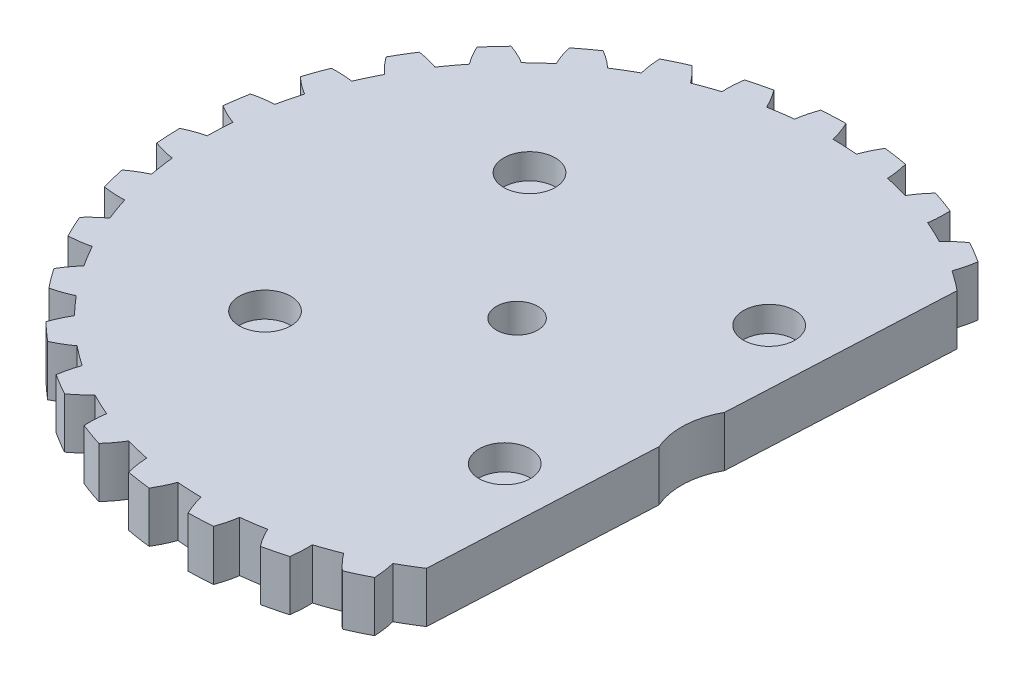
SolidWorks part; units mm, degrees
ref_plane "正面" through (0, 0, 0) normal (0, 0, 1) x (1, 0, 0)
ref_plane "平面" through (0, 0, 0) normal (0, 1, 0) x (1, 0, 0)
ref_plane "右側面" through (0, 0, 0) normal (1, 0, 0) x (0, 0, -1)
sketch "ｽｹｯﾁ1" plane through (0, 0, 0) normal (0, 1, 0) x (1, 0, 0)
  line L0 (0, 0) -> (0, 104.1615) construction
  line L1 (-93.5954, 64) -> (78.777, 64) construction
  line L2 (-63.9379, 40.7285) -> (71.1281, 89.8885) construction
  circle A0 centre (0, 0) radius 64 construction
  circle A1 centre (0, 0) radius 60.1403 construction
  point P7 (0, 64)
  dimension "D1" = 128
  dimension "D2" = 20
sketch "ｽｹｯﾁ2" plane through (0, 0, 0) normal (0, 1, 0) x (1, 0, 0)
  line L0 (-20.5692, 56.5134) -> (0, 64) construction
  line L1 (-14.8381, 58.2811) -> (0.56, 62.2014) construction
  line L2 (-15.8051, 58.0264) -> (0.4905, 62.4649) construction
  line L3 (-16.7677, 57.7555) -> (0.4122, 62.7433) construction
  line L4 (-17.7257, 57.4688) -> (0.3245, 63.0362) construction
  line L5 (-18.6788, 57.1661) -> (0.2269, 63.3434) construction
  line L6 (-19.6267, 56.8476) -> (0.1189, 63.6648) construction
  line L7 (-21.506, 56.1636) -> (-0.1303, 64.3487) construction
  line L8 (-22.4369, 55.7983) -> (-0.2724, 64.7108) construction
  line L9 (-23.3615, 55.4175) -> (-0.4268, 65.0857) construction
  line L10 (-24.2797, 55.0214) -> (-0.594, 65.4734) construction
  line L11 (-25.1912, 54.6101) -> (-0.7745, 65.8733) construction
  line L12 (-26.0957, 54.1837) -> (-0.9688, 66.2852) construction
  line L14 (0, 0) -> (-5.2283, 106.4246) construction
  line L15 (0, 0) -> (0, 104.1615) construction
  circle A0 centre (0, 0) radius 60.1403 construction
  arc A1 (-20.5692, 56.5134) -> (-19.6267, 56.8476) centre (0, 0) cw
  arc A2 (-19.6267, 56.8476) -> (-18.6788, 57.1661) centre (0, 0) cw
  arc A3 (-18.6788, 57.1661) -> (-17.7257, 57.4688) centre (0, 0) cw
  arc A4 (-17.7257, 57.4688) -> (-16.7677, 57.7555) centre (0, 0) cw
  arc A5 (-16.7677, 57.7555) -> (-15.8051, 58.0264) centre (0, 0) cw
  arc A6 (-15.8051, 58.0264) -> (-14.8381, 58.2811) centre (0, 0) cw
  arc A7 (-20.5692, 56.5134) -> (-21.506, 56.1636) centre (0, 0) ccw
  arc A8 (-21.506, 56.1636) -> (-22.4369, 55.7983) centre (0, 0) ccw
  arc A9 (-22.4369, 55.7983) -> (-23.3615, 55.4175) centre (0, 0) ccw
  arc A10 (-23.3615, 55.4175) -> (-24.2797, 55.0214) centre (0, 0) ccw
  arc A11 (-24.2797, 55.0214) -> (-25.1912, 54.6101) centre (0, 0) ccw
  arc A12 (-25.1912, 54.6101) -> (-26.0957, 54.1837) centre (0, 0) ccw
  arc A13 (-20.5692, 56.5134) -> (0.8963, 60.1336) centre (0, 0) cw
  circle A14 centre (0, 0) radius 66 construction
  circle A16 centre (0, 0) radius 64 construction
  spline S0 degree 3 poles (-0.9688, 66.2852) (-0.8394, 66.0167) (-0.6553, 65.6183) (-0.4279, 65.0913) (-0.2734, 64.7163) (-0.1313, 64.3543) (-0.0009, 64.0056) (0.118, 63.6704) (0.226, 63.349) (0.3237, 63.0417) (0.4114, 62.7488) (0.6791, 61.7983) (0.8527, 60.9277) (0.8963, 60.1336) knots 0 0 0 0 0.138368 0.203693 0.266445 0.326623 0.384229 0.439262 0.491722 0.541609 0.588924 0.633665 1 1 1 1
  spline S1 degree 3 poles (-5.533, 66.061) (-5.6354, 65.7811) (-5.7795, 65.3666) (-5.9542, 64.8198) (-6.0712, 64.4315) (-6.1772, 64.0573) (-6.2727, 63.6974) (-6.3582, 63.3522) (-6.4342, 63.0218) (-6.5013, 62.7064) (-6.5599, 62.4063) (-6.7331, 61.4341) (-6.8206, 60.5507) (-6.7861, 59.7562) knots 0 0 0 0 0.138368 0.203693 0.266445 0.326623 0.384229 0.439262 0.491722 0.541609 0.588924 0.633665 1 1 1 1
  dimension "D1" = 21.8893
  dimension "D3" = 19.8893
  dimension "D4" = 20.8893
  dimension "D5" = 18.8893
  dimension "D6" = 17.8893
  dimension "D7" = 16.8893
  dimension "D8" = 15.8893
  dimension "D9" = 22.8893
  dimension "D10" = 23.8893
  dimension "D11" = 24.8893
  dimension "D12" = 25.8893
  dimension "D13" = 26.8893
  dimension "D14" = 27.8893
  dimension "D15" = 2.813
  dimension "D16" = 2
  dimension "D2" = 1
sketch "ｽｹｯﾁ3" plane through (0, 0, 0) normal (0, 1, 0) x (1, 0, 0)
  arc A1 (0.6104, 61.997) -> (-6.6843, 61.6386) centre (0, 0) ccw
  arc A3 (-0.8309, 65.9948) -> (-5.6417, 65.7584) centre (0, 0) ccw
  spline S2 degree 3 poles (-5.533, 66.061) (-5.6354, 65.7811) (-5.7795, 65.3666) (-5.9542, 64.8198) (-6.0712, 64.4315) (-6.1772, 64.0573) (-6.2727, 63.6974) (-6.3582, 63.3522) (-6.4342, 63.0218) (-6.5013, 62.7064) (-6.5599, 62.4063) (-6.7331, 61.4341) (-6.8206, 60.5507) (-6.7861, 59.7562) knots 0 0 0 0 0.138368 0.203693 0.266445 0.326623 0.384229 0.439262 0.491722 0.541609 0.588924 0.633665 1 1 1 1 construction
  spline S3 degree 3 poles (-0.9688, 66.2852) (-0.8394, 66.0167) (-0.6553, 65.6183) (-0.4279, 65.0913) (-0.2734, 64.7163) (-0.1313, 64.3543) (-0.0009, 64.0056) (0.118, 63.6704) (0.226, 63.349) (0.3237, 63.0417) (0.4114, 62.7488) (0.6791, 61.7983) (0.8527, 60.9277) (0.8963, 60.1336) knots 0 0 0 0 0.138368 0.203693 0.266445 0.326623 0.384229 0.439262 0.491722 0.541609 0.588924 0.633665 1 1 1 1 construction
  spline S4 degree 3 poles (-5.6417, 65.7584) (-5.7052, 65.5784) (-5.8121, 65.2645) (-5.9542, 64.8198) (-6.0712, 64.4315) (-6.1772, 64.0573) (-6.2727, 63.6974) (-6.3582, 63.3522) (-6.4342, 63.0218) (-6.5013, 62.7064) (-6.5599, 62.4063) (-6.6229, 62.0526) (-6.6623, 61.7982) (-6.6843, 61.6386) knots 0 0 0 0 0.134544 0.233721 0.328992 0.420358 0.507816 0.591369 0.671015 0.746755 0.818588 0.886516 1 1 1 1
  spline S5 degree 3 poles (-0.8309, 65.9948) (-0.7501, 65.8218) (-0.6129, 65.5199) (-0.4279, 65.0913) (-0.2734, 64.7163) (-0.1313, 64.3543) (-0.0009, 64.0056) (0.118, 63.6704) (0.226, 63.349) (0.3237, 63.0417) (0.4114, 62.7488) (0.5088, 62.4029) (0.573, 62.1536) (0.6104, 61.997) knots 0 0 0 0 0.134544 0.233721 0.328992 0.420358 0.507816 0.591369 0.671015 0.746755 0.818588 0.886516 1 1 1 1
  point P3 (-5.6417, 65.7584)
  point P4 (-0.8309, 65.9948)
  point P5 (0.6104, 61.997)
  point P6 (-6.6843, 61.6386)
  dimension "D1" = 124
  dimension "D2" = 4
sketch "ｽｹｯﾁ5" plane through (0, 0, 0) normal (0, 1, 0) x (1, 0, 0)
  circle A0 centre (0, 0) radius 62
  dimension "D1" = 124
extrude "ﾎﾞｽ - 押し出し5" add sketch "ｽｹｯﾁ5" along normal blind 10
extrude "ﾎﾞｽ - 押し出し6" add sketch "ｽｹｯﾁ3" along normal blind 10
pattern_circular "円形ﾊﾟﾀｰﾝ3" count 32 over 360 about axis through (0, 10, 0) along (0, 1, 0) of "ﾎﾞｽ - 押し出し6"
sketch "ｽｹｯﾁ6" plane through (0, 10, 0) normal (0, 1, 0) x (1, 0, 0)
  line L0 (3.0422, 61.9253) -> (-2450.3415, -49877.8475) construction
  line L1 (-1.6979, 0.0834) -> (-49935.7979, 2453.1884) construction
  circle A0 centre (-23.7432, 26.1966) radius 5.1
  arc A4 (5.4693, 61.7583) -> (0.6104, 61.997) centre (0, 0) ccw construction
  arc A5 (-5.4693, -61.7583) -> (-0.6104, -61.997) centre (0, 0) ccw construction
  arc A6 (-61.7583, 5.4693) -> (-61.997, 0.6104) centre (0, 0) ccw construction
  circle A7 centre (26.1966, 23.7432) radius 5.1
  circle A8 centre (23.7432, -26.1966) radius 5.1
  circle A9 centre (-26.1966, -23.7432) radius 5.1
  point P14 (-61.9253, 3.0422)
  point P24 (3.0422, 61.9253)
  point P28 (-3.0422, -61.9253)
  dimension "D5" = 10.2
  dimension "D1" = 25
  dimension "D2" = 25
extrude "ｶｯﾄ - 押し出し1" cut sketch "ｽｹｯﾁ6" against normal blind 5
sketch "ｽｹｯﾁ7" plane through (0, 10, 0) normal (0, 1, 0) x (1, 0, 0)
  line L12 (-61.9253, 3.0422) -> (49877.8475, -2450.3415) construction
  line L13 (39.0975, 53.1732) -> (36.701, 4.3914)
  line L14 (33.6973, -56.7494) -> (63.2204, -58.1998)
  line L16 (39.0975, 53.1732) -> (68.6206, 51.7228)
  line L18 (36.0938, -7.9676) -> (33.6973, -56.7494)
  line L19 (68.6206, 51.7228) -> (63.2204, -58.1998)
  arc A1 (-61.7583, 5.4693) -> (-61.997, 0.6104) centre (0, 0) ccw construction
  arc A2 (61.7583, -5.4693) -> (61.997, -0.6104) centre (0, 0) ccw construction
  circle A3 centre (0, 0) radius 66 construction
  arc A4 (36.701, 4.3914) -> (36.0938, -7.9676) centre (48.941, -2.4043) ccw
  circle A5 centre (0, 0) radius 4.1
  point P4 (74.1945, 52.7214)
  point P10 (-61.9253, 3.0422)
  point P16 (61.9253, -3.0422)
  dimension "D1" = 49
  dimension "D2" = 14
  dimension "D3" = 132
  dimension "D4" = 8.2
extrude "ｶｯﾄ - 押し出し2" cut sketch "ｽｹｯﾁ7" against normal through all
equation "\"D3@ｽｹｯﾁ2\"=\"D4@ｽｹｯﾁ2\"-\"D2@ｽｹｯﾁ2\""
equation "\"D4@ｽｹｯﾁ2\"=\"D1@ｽｹｯﾁ2\"-\"D2@ｽｹｯﾁ2\""
equation "\"D5@ｽｹｯﾁ2\"=\"D3@ｽｹｯﾁ2\"-\"D2@ｽｹｯﾁ2\""
equation "\"D6@ｽｹｯﾁ2\"=\"D5@ｽｹｯﾁ2\"-\"D2@ｽｹｯﾁ2\""
equation "\"D7@ｽｹｯﾁ2\"=\"D6@ｽｹｯﾁ2\"-\"D2@ｽｹｯﾁ2\""
equation "\"D8@ｽｹｯﾁ2\"=\"D7@ｽｹｯﾁ2\"-\"D2@ｽｹｯﾁ2\""
equation "\"D9@ｽｹｯﾁ2\"=\"D1@ｽｹｯﾁ2\"+\"D2@ｽｹｯﾁ2\""
equation "\"D10@ｽｹｯﾁ2\"=\"D9@ｽｹｯﾁ2\"+\"D2@ｽｹｯﾁ2\""
equation "\"D11@ｽｹｯﾁ2\"=\"D10@ｽｹｯﾁ2\"+\"D2@ｽｹｯﾁ2\""
equation "\"D12@ｽｹｯﾁ2\"=\"D11@ｽｹｯﾁ2\"+\"D2@ｽｹｯﾁ2\""
equation "\"D13@ｽｹｯﾁ2\"=\"D12@ｽｹｯﾁ2\"+\"D2@ｽｹｯﾁ2\""
equation "\"D14@ｽｹｯﾁ2\"=\"D13@ｽｹｯﾁ2\"+\"D2@ｽｹｯﾁ2\""
equation "\"D15@ｽｹｯﾁ2\"=90/32"
